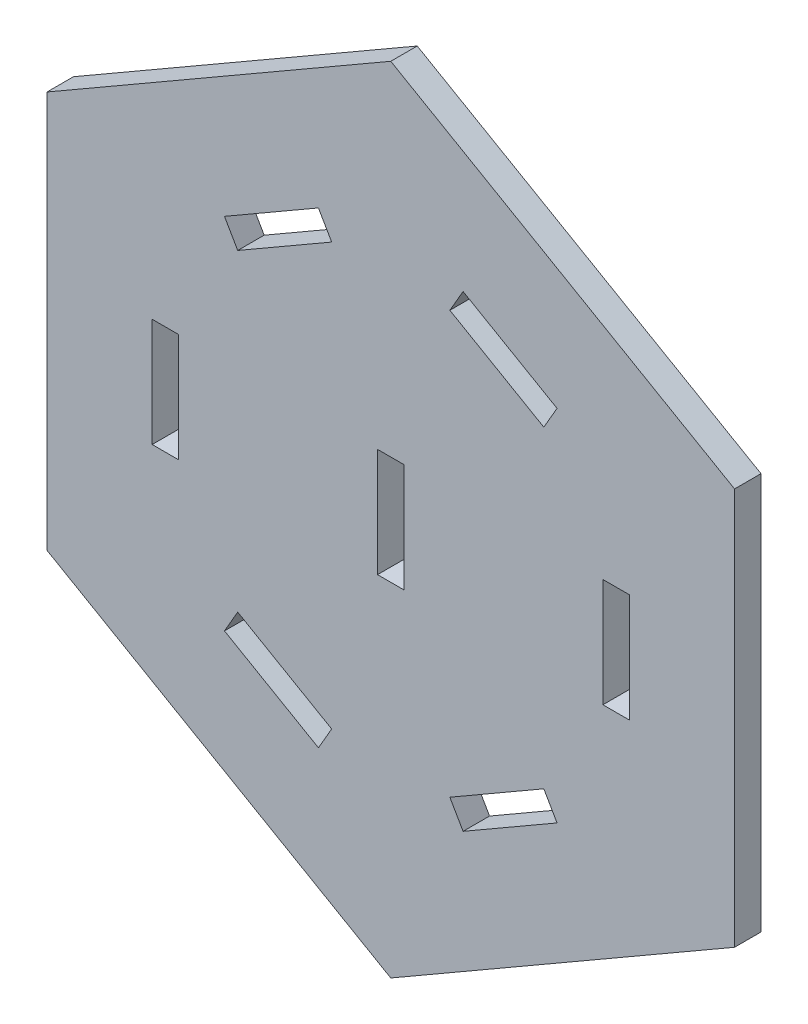
SolidWorks part; units mm, degrees
ref_plane "Alzado" through (0, 0, 0) normal (0, 0, 1) x (1, 0, 0)
ref_plane "Planta" through (0, 0, 0) normal (0, 1, 0) x (1, 0, 0)
ref_plane "Vista lateral" through (0, 0, 0) normal (1, 0, 0) x (0, 0, -1)
sketch "Croquis1" plane through (0, 0, 0) normal (0, 0, 1) x (1, 0, 0)
  line L0 (318.6419, 349.4485) -> (694.6419, 349.4485) construction
  line L23 (307.2597, 25.95) -> (346.2308, 48.45)
  line L24 (346.2308, 48.45) -> (346.2308, 93.45)
  line L25 (346.2308, 93.45) -> (307.2597, 115.95)
  line L55 (307.2597, 98.72) -> (283.2102, 84.835) construction
  line L56 (283.2102, 84.835) -> (283.2102, 57.065) construction
  line L57 (283.2102, 57.065) -> (307.2597, 43.18) construction
  line L58 (307.2597, 43.18) -> (331.3092, 57.065) construction
  line L59 (331.3092, 57.065) -> (331.3092, 64.8) construction
  line L60 (331.3092, 84.835) -> (307.2597, 98.72) construction
  line L61 (305.7597, 77.1) -> (308.7597, 77.1)
  line L62 (305.7597, 77.1) -> (305.7597, 64.8)
  line L63 (305.7597, 64.8) -> (308.7597, 64.8)
  line L64 (308.7597, 77.1) -> (308.7597, 64.8)
  line L65 (305.7597, 77.1) -> (308.7597, 64.8) construction
  line L66 (305.7597, 64.8) -> (308.7597, 77.1) construction
  line L67 (331.3092, 77.1) -> (334.3092, 77.1)
  line L69 (331.3092, 64.8) -> (334.3092, 64.8)
  line L70 (334.3092, 77.1) -> (334.3092, 64.8)
  line L71 (331.3092, 77.1) -> (331.3092, 84.835) construction
  line L73 (331.3092, 77.1) -> (331.3092, 64.8)
  line L74 (307.2597, 72.0016) -> (307.2597, 69.559) construction
  line L75 (283.2102, 64.8) -> (280.2102, 64.8)
  line L76 (280.2102, 77.1) -> (280.2102, 64.8)
  line L77 (283.2102, 77.1) -> (280.2102, 77.1)
  line L78 (283.2102, 77.1) -> (283.2102, 64.8)
  line L79 (313.9584, 94.8525) -> (324.6105, 88.7025)
  line L80 (313.9584, 94.8525) -> (315.4584, 97.4506)
  line L81 (324.6105, 88.7025) -> (326.1105, 91.3006)
  line L82 (315.4584, 97.4506) -> (326.1105, 91.3006)
  line L83 (307.2597, 102.0142) -> (307.2597, 92.5518) construction
  line L84 (305.2148, 70.95) -> (309.804, 70.95) construction
  line L85 (289.9089, 88.7025) -> (288.4089, 91.3006)
  line L86 (299.061, 97.4506) -> (288.4089, 91.3006)
  line L87 (300.561, 94.8525) -> (299.061, 97.4506)
  line L88 (300.561, 94.8525) -> (289.9089, 88.7025)
  line L89 (300.561, 47.0475) -> (289.9089, 53.1975)
  line L90 (300.561, 47.0475) -> (299.061, 44.4494)
  line L91 (299.061, 44.4494) -> (288.4089, 50.5994)
  line L92 (289.9089, 53.1975) -> (288.4089, 50.5994)
  line L93 (324.6105, 53.1975) -> (326.1105, 50.5994)
  line L94 (315.4584, 44.4494) -> (326.1105, 50.5994)
  line L95 (313.9584, 47.0475) -> (315.4584, 44.4494)
  line L96 (313.9584, 47.0475) -> (324.6105, 53.1975)
  line L97 (307.2597, 115.95) -> (268.2885, 93.45)
  line L98 (268.2885, 93.45) -> (268.2885, 48.45)
  line L99 (268.2885, 48.45) -> (307.2597, 25.95)
  circle A0 centre (307.2597, 70.95) radius 38.9711 construction
  circle A1 centre (307.2597, 70.95) radius 24.0495 construction
  dimension "D2" = 45
  dimension "D13" = 12.3
  dimension "D14" = 3
  dimension "D15" = 12.3
  dimension "D16" = 3
  dimension "D17" = 3
  dimension "D18" = 12.3
  dimension "D19" = 6.15
extrude "Saliente-Extruir1" add sketch "Croquis1" along normal blind 3
